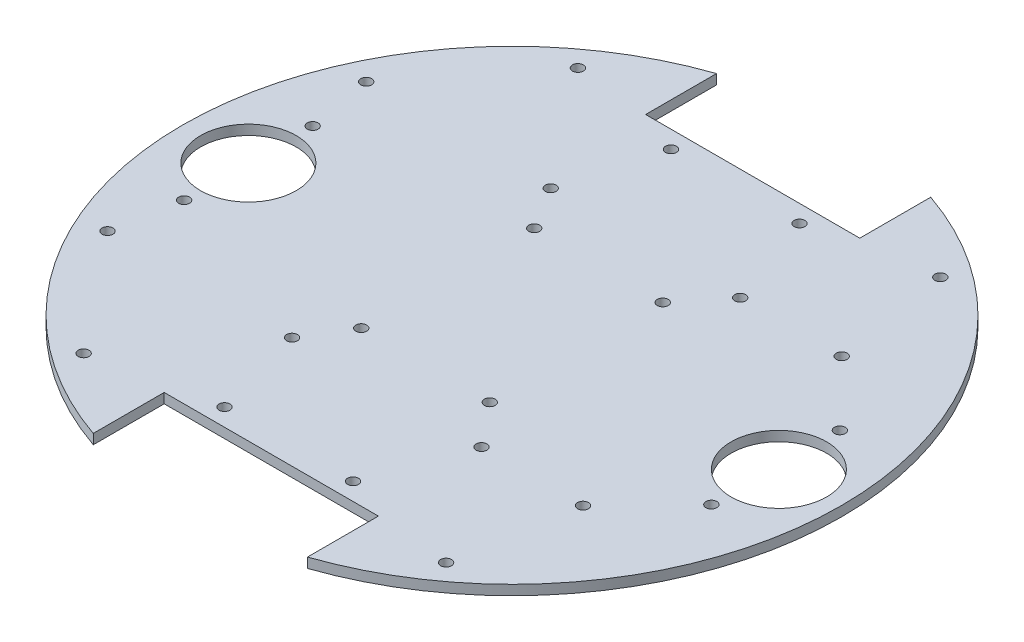
SolidWorks part; units mm, degrees
ref_plane "Alzado" through (0, 0, 0) normal (0, 0, 1) x (1, 0, 0)
ref_plane "Planta" through (0, 0, 0) normal (0, 1, 0) x (1, 0, 0)
ref_plane "Vista lateral" through (0, 0, 0) normal (1, 0, 0) x (0, 0, -1)
sketch "Croquis1" plane through (0, 0, 0) normal (0, 1, 0) x (1, 0, 0)
  line L0 (0, 107.6812) -> (0, -106.0496) construction
  line L1 (-32.5, -73.0475) -> (32.5, -73.0475)
  line L2 (-32.5, -73.0475) -> (-32.5, -94.5714)
  line L4 (32.5, -73.0475) -> (32.5, -94.5714)
  line L5 (0, 0) -> (54.5026, 0) construction
  line L15 (-32.5, 73.0475) -> (-32.5, 94.5714)
  line L19 (-32.5, 73.0475) -> (32.5, 73.0475)
  line L20 (32.5, 73.0475) -> (32.5, 94.5714)
  arc A0 (-32.5, 94.5714) -> (-32.5, -94.5714) centre (0, 0) ccw
  arc A1 (32.5, -94.5714) -> (32.5, 94.5714) centre (0, 0) ccw
  circle A2 centre (-80, 19.5) radius 1.65
  circle A3 centre (-80, -19.5) radius 1.65
  circle A4 centre (80, -19.5) radius 1.65
  circle A5 centre (80, 19.5) radius 1.65
  circle A6 centre (55, 75) radius 1.65
  circle A7 centre (-55, 75) radius 1.65
  circle A8 centre (55, -75) radius 1.65
  circle A9 centre (-55, -75) radius 1.65
  circle A10 centre (-80, 0) radius 14.5
  circle A11 centre (80.9909, 0) radius 14.5
  circle A34 centre (-19.5, -67.7475) radius 1.65
  circle A36 centre (19.5, -67.7475) radius 1.65
  circle A37 centre (-19.5, -26.2475) radius 1.65
  circle A38 centre (19.5, -26.2475) radius 1.65
  circle A39 centre (19.5, 26.2475) radius 1.65
  circle A40 centre (-19.5, 26.2475) radius 1.65
  circle A41 centre (-19.5, 67.7475) radius 1.65
  circle A42 centre (19.5, 67.7475) radius 1.65
  circle A43 centre (-27.5, -39.2475) radius 1.65
  circle A44 centre (-83.5, -39.2475) radius 1.65
  circle A46 centre (60.8, -39.2475) radius 1.65
  circle A47 centre (30, -39.2475) radius 1.65
  circle A50 centre (-27.5, 39.2475) radius 1.65
  circle A51 centre (-83.5, 39.2475) radius 1.65
  circle A52 centre (60.8, 39.2475) radius 1.65
  circle A53 centre (30, 39.2475) radius 1.65
  dimension "D1" = 200
  dimension "D10" = 3.3
  dimension "D14" = 30.8
  dimension "D16" = 29
  dimension "D17" = 29
  dimension "D5" = 13
  dimension "D6" = 5.3
  dimension "D7" = 13
  dimension "D8" = 2
  dimension "D15" = 3.3
  dimension "D9" = 3.3
  dimension "D3" = 8
  dimension "D11" = 19.5
  dimension "D12" = 80
  dimension "D13" = 56
  dimension "D18" = 10.5
  dimension "D19" = 80
  dimension "D20" = 75
  dimension "D21" = 55
  dimension "D22" = 13
  dimension "D44" = 73.0475
  dimension "D48" = 65
extrude "Saliente-Extruir1" add sketch "Croquis1" along normal blind 3
sketch "Croquis2" plane through (0, 0, 0) normal (0, -1, 0) x (1, 0, 0)
  line L0 (-49, 3.9577) -> (49, 3.9577) construction
  text T0 "ITAM\r\nIngeniería" font "@Adobe Song Std L" height 14
  dimension "D1" = 98
  dimension "D2" = 49
extrude "Cortar-Extruir1" cut sketch "Croquis2" against normal blind 1
